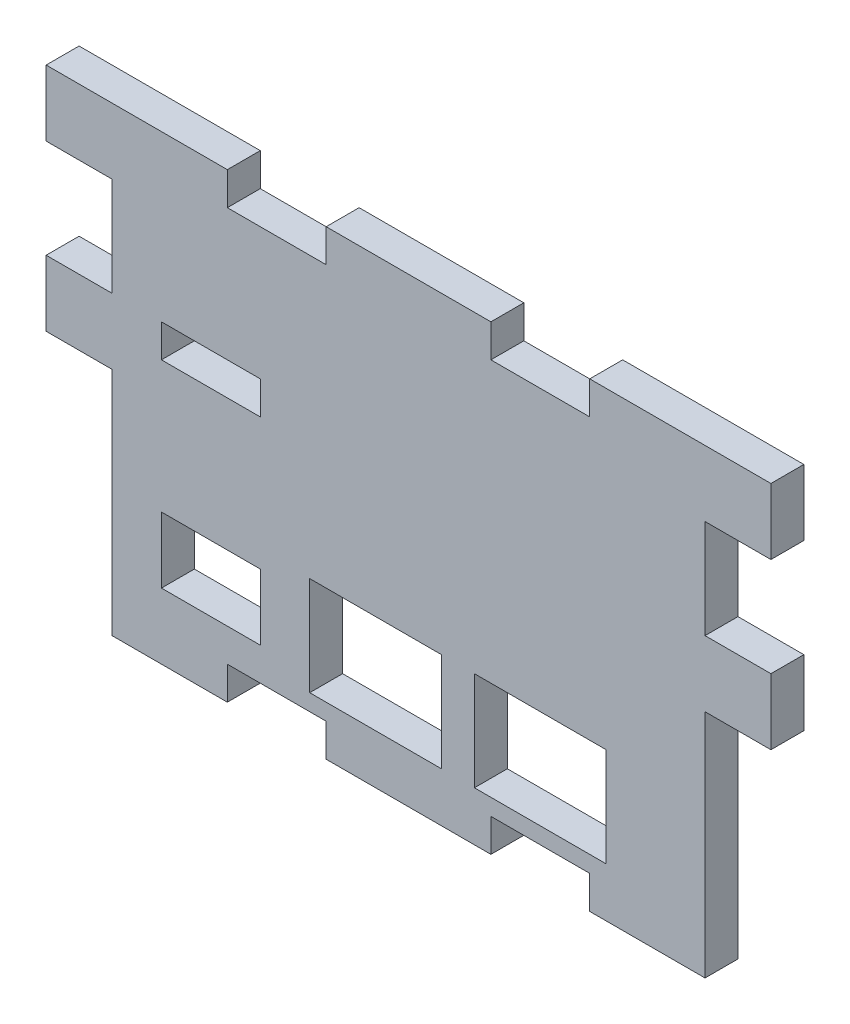
SolidWorks part; units mm, degrees
ref_plane "Plan de face" through (0, 0, 0) normal (0, 0, 1) x (1, 0, 0)
ref_plane "Plan de dessus" through (0, 0, 0) normal (0, 1, 0) x (1, 0, 0)
ref_plane "Plan de droite" through (0, 0, 0) normal (1, 0, 0) x (0, 0, -1)
sketch "Esquisse1" plane through (0, 0, 0) normal (0, 0, 1) x (1, 0, 0)
  line L1 (-55, 35) -> (55, 35)
  line L2 (-55, 35) -> (-55, -35)
  line L3 (-55, -35) -> (55, -35)
  line L4 (55, 35) -> (55, -35)
  line L5 (-55, 35) -> (55, -35) construction
  line L6 (-55, -35) -> (55, 35) construction
  point P0 (0, 0)
  dimension "D1" = 70
  dimension "D2" = 110
extrude "Boss.-Extru.1" add sketch "Esquisse1" along normal blind 5
sketch "Esquisse2" plane through (0, 0, 5) normal (0, 0, 1) x (1, 0, 0)
  line L0 (-55, -35) -> (55, -35) construction
  line L1 (10, -12.5) -> (30, -12.5)
  line L2 (10, -12.5) -> (10, -27.5)
  line L3 (10, -27.5) -> (30, -27.5)
  line L4 (30, -12.5) -> (30, -27.5)
  line L5 (10, -12.5) -> (30, -27.5) construction
  line L6 (10, -27.5) -> (30, -12.5) construction
  line L7 (-15, -12.5) -> (5, -12.5)
  line L8 (-15, -12.5) -> (-15, -27.5)
  line L9 (-15, -27.5) -> (5, -27.5)
  line L10 (5, -12.5) -> (5, -27.5)
  line L11 (-15, -12.5) -> (5, -27.5) construction
  line L12 (-15, -27.5) -> (5, -12.5) construction
  line L13 (-37.5, -15) -> (-22.5, -15)
  line L14 (-37.5, -15) -> (-37.5, -25)
  line L15 (-37.5, -25) -> (-22.5, -25)
  line L16 (-22.5, -15) -> (-22.5, -25)
  line L17 (-37.5, -15) -> (-22.5, -25) construction
  line L18 (-37.5, -25) -> (-22.5, -15) construction
  line L19 (55, -35) -> (55, 35) construction
  line L20 (-55, 35) -> (-55, -35) construction
  line L22 (-37.5, 10) -> (-22.5, 10)
  line L23 (-37.5, 10) -> (-37.5, 5)
  line L24 (-37.5, 5) -> (-22.5, 5)
  line L25 (-22.5, 10) -> (-22.5, 5)
  line L26 (-37.5, 10) -> (-22.5, 5) construction
  line L27 (-37.5, 5) -> (-22.5, 10) construction
  point P0 (20, -20)
  point P5 (-5, -20)
  point P10 (-30, -20)
  point P23 (-30, 7.5)
  dimension "D1" = 15
  dimension "D2" = 20
  dimension "D3" = 20
  dimension "D4" = 15
  dimension "D5" = 15
  dimension "D6" = 10
  dimension "D7" = 25
  dimension "D8" = 15
  dimension "D9" = 35
  dimension "D10" = 15
  dimension "D11" = 25
  dimension "D12" = 5
  dimension "D13" = 15
  dimension "D14" = 20
extrude "Enlèv. mat.-Extru.1" cut sketch "Esquisse2" against normal blind 5
sketch "Esquisse6" plane through (0, 0, 0) normal (0, 0, -1) x (-1, 0, 0)
  line L0 (-55, 35) -> (55, 35) construction
  line L1 (-55, -35) -> (-45, -35)
  line L2 (-55, -35) -> (-55, 0)
  line L3 (-55, 0) -> (-45, 0)
  line L4 (-45, -35) -> (-45, 0)
  line L5 (55, 35) -> (55, -35) construction
  line L6 (55, -35) -> (45, -35)
  line L7 (55, -35) -> (55, 0)
  line L8 (55, 0) -> (45, 0)
  line L9 (45, -35) -> (45, 0)
  line L10 (-55, 25) -> (-45, 25)
  line L11 (-55, 25) -> (-55, 10)
  line L12 (-55, 10) -> (-45, 10)
  line L13 (-45, 25) -> (-45, 10)
  line L14 (55, 25) -> (45, 25)
  line L15 (55, 25) -> (55, 10)
  line L16 (55, 10) -> (45, 10)
  line L17 (45, 25) -> (45, 10)
  line L18 (-55, -35) -> (-55, 35) construction
  line L19 (55, -35) -> (-55, -35) construction
  line L20 (-27.5, 35) -> (-12.5, 35)
  line L21 (-27.5, 35) -> (-27.5, 30)
  line L22 (-27.5, 30) -> (-12.5, 30)
  line L23 (-12.5, 35) -> (-12.5, 30)
  line L24 (12.5, 35) -> (27.5, 35)
  line L25 (12.5, 35) -> (12.5, 30)
  line L26 (12.5, 30) -> (27.5, 30)
  line L27 (27.5, 35) -> (27.5, 30)
  line L28 (-27.5, -35) -> (-12.5, -35)
  line L29 (-27.5, -35) -> (-27.5, -30)
  line L30 (-27.5, -30) -> (-12.5, -30)
  line L31 (-12.5, -35) -> (-12.5, -30)
  line L33 (12.5, -35) -> (27.5, -35)
  line L34 (12.5, -35) -> (12.5, -30)
  line L35 (12.5, -30) -> (27.5, -30)
  line L36 (27.5, -35) -> (27.5, -30)
  dimension "D1" = 35
  dimension "D2" = 10
  dimension "D3" = 10
  dimension "D4" = 35
  dimension "D5" = 15
  dimension "D6" = 10
  dimension "D7" = 15
  dimension "D8" = 10
  dimension "D9" = 10
  dimension "D10" = 10
  dimension "D11" = 5
  dimension "D12" = 5
  dimension "D13" = 15
  dimension "D14" = 15
  dimension "D15" = 25
  dimension "D16" = 27.5
extrude "Enlèv. mat.-Extru.2" cut sketch "Esquisse6" against normal blind 5
